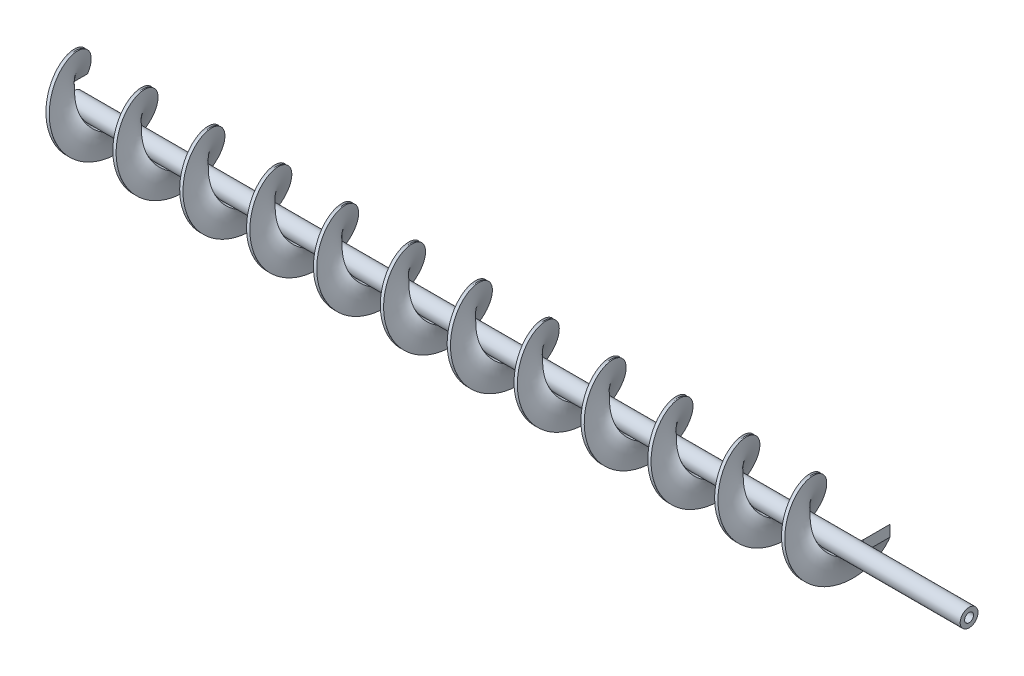
SolidWorks part; units mm, degrees
ref_plane "Vorderansicht" through (0, 0, 0) normal (0, 0, 1) x (1, 0, 0)
ref_plane "Draufsicht" through (0, 0, 0) normal (0, 1, 0) x (1, 0, 0)
ref_plane "Seitenansicht" through (0, 0, 0) normal (1, 0, 0) x (0, 0, -1)
sketch "Skizze3" plane through (0, 0, 0) normal (1, 0, 0) x (0, 0, -1)
  circle A0 centre (0, 0) radius 4
  circle A1 centre (0, 0) radius 2
  dimension "D1" = 8
  dimension "D2" = 2
extrude "Aufsatz-Linear austragen1" add sketch "Skizze3" against normal blind 350 and the other way blind 51.5 separate body
sketch "Skizze1" plane through (0, 0, 0) normal (1, 0, 0) x (0, 0, -1)
  circle A0 centre (0, 0) radius 4
  dimension "D1" = 8
curve "Spirale/Helix1" pitch 30 height 360 turns 12
sketch "Skizze2" plane through (0, 0, 0) normal (1, 0, 0) x (0, 0, -1)
  line L0 (19.3938, 0) -> (56.2084, 0) construction
  line L2 (4, -2.5) -> (16, -2.5)
  line L3 (4, -2.5) -> (4, 2.5)
  line L4 (4, 2.5) -> (16, 2.5)
  line L5 (16, -2.5) -> (16, 2.5)
  dimension "D1" = 16
  dimension "D2" = 4
  dimension "D3" = 5
sweep "Austragung1" add profiles "Skizze2" path "Spirale/Helix1"
